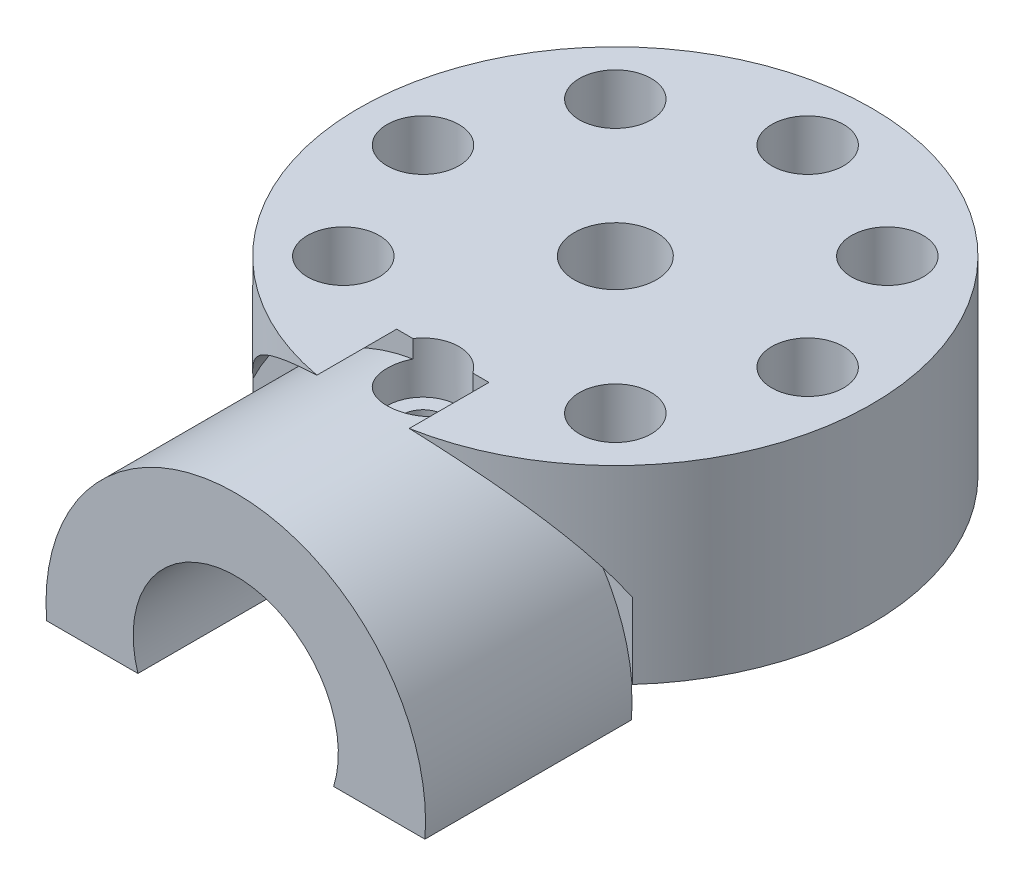
SolidWorks part; units mm, degrees
ref_plane "前视基准面" through (0, 0, 0) normal (0, 0, 1) x (1, 0, 0)
ref_plane "上视基准面" through (0, 0, 0) normal (0, 1, 0) x (1, 0, 0)
ref_plane "右视基准面" through (0, 0, 0) normal (1, 0, 0) x (0, 0, -1)
other "Configuration Table"
sketch "草图1" plane through (0, 0, 0) normal (0, 1, 0) x (1, 0, 0)
  line L0 (-25, 0) -> (25, 0) construction
  line L1 (0, 25) -> (0, -25) construction
  arc A2 (0, 25) -> (-25, 0) centre (0, 0) ccw
  arc A3 (-25, 0) -> (0, -25) centre (0, 0) ccw
  arc A4 (0, -25) -> (25, 0) centre (0, 0) ccw
  arc A5 (25, 0) -> (0, 25) centre (0, 0) ccw
  dimension "D1" = 25
  dimension "D2" = 90
extrude "凸台-拉伸2" add sketch "草图1" along normal blind 18.5
sketch "草图4" plane through (0, 0, 0) normal (0, 0, 1) x (1, 0, 0)
  line L0 (0, 0) -> (0, -1.5) construction
  line L1 (-25, 0) -> (25, 0) construction
  line L2 (-18.4391, 0) -> (18.4391, 0)
  arc A0 (-18.4391, 0) -> (18.4391, 0) centre (0, -1.5) cw
  dimension "D2" = 18.5
  dimension "D1" = 1.5
extrude "凸台-拉伸3" add sketch "草图4" along normal blind 37 contours A0 L2
sketch "草图7" plane through (0, 0, 0) normal (0, -1, 0) x (1, 0, 0)
  line L0 (-1000, 0) -> (49000, 0) construction
  line L1 (0, -1000) -> (0, 49000) construction
  line L2 (-707.1068, -707.1068) -> (34648.2323, 34648.2323) construction
  circle A0 centre (0, 0) radius 4
  circle A1 centre (0, 0) radius 18.75 construction
  circle A3 centre (18.75, 0) radius 2
  circle A4 centre (13.2583, 13.2583) radius 2
  circle A5 centre (0, 18.75) radius 2
  circle A6 centre (-18.75, 0) radius 2
  circle A7 centre (-13.2583, 13.2583) radius 2
  circle A8 centre (13.2583, -13.2583) radius 2
  circle A9 centre (0, -18.75) radius 2
  circle A10 centre (-13.2583, -13.2583) radius 2
  dimension "D1" = 37.5
  dimension "D2" = 8
  dimension "D4" = 4
  dimension "D5" = 4
  dimension "D3" = 45
extrude "切除-拉伸1" cut sketch "草图7" against normal through all
sketch "草图8" plane through (0, 0, 37) normal (0, 0, 1) x (1, 0, 0)
  line L0 (-18.4391, 0) -> (18.4391, 0)
  line L3 (18.4391, -3) -> (-18.4391, -3)
  line L4 (0, 0) -> (0, -3) construction
  arc A0 (18.4391, -3) -> (18.4391, 0) centre (0, -1.5) ccw
  arc A1 (-18.4391, 0) -> (-18.4391, -3) centre (0, -1.5) ccw
  dimension "D2" = 18.5
  dimension "D1" = 3
extrude "凸台-拉伸5" add sketch "草图8" against normal up to vertex
sketch "草图9" plane through (0, -3, 0) normal (0, -1, 0) x (1, 0, 0)
  circle A0 centre (0, 0) radius 25
extrude "切除-拉伸2" cut sketch "草图9" against normal up to surface (3 mm away) up to face at (0, 0, -4)
sketch "草图10" plane through (0, 0, 16.8152) normal (0, 0, 1) x (1, 0, 0)
  line L0 (0, 0) -> (0, -1.5) construction
  circle A2 centre (0, -1.5) radius 20.5
  circle A3 centre (0, -1.5) radius 18.5
  dimension "D2" = 37
  dimension "D3" = 41
  dimension "D1" = 1.5
extrude "切除-拉伸3" cut sketch "草图10" along normal up to surface (20.1848 mm away) up to face at (0, 7, 37)
sketch "草图11" plane through (0, 18.5, 0) normal (0, 1, 0) x (1, 0, 0)
  circle A0 centre (0, 18.75) radius 3.5
  circle A1 centre (13.2583, 13.2583) radius 3.5
  circle A2 centre (18.75, 0) radius 3.5
  circle A3 centre (13.2583, -13.2583) radius 3.5
  circle A4 centre (0, -18.75) radius 3.5
  circle A5 centre (-13.2583, -13.2583) radius 3.5
  circle A6 centre (-18.75, 0) radius 3.5
  circle A7 centre (-13.2583, 13.2583) radius 3.5
  dimension "D1" = 7
  dimension "D2" = 7
  dimension "D3" = 7
  dimension "D4" = 7
  dimension "D5" = 7
  dimension "D6" = 7
  dimension "D7" = 7
  dimension "D8" = 7
extrude "切除-拉伸4" cut sketch "草图11" against normal blind 5
sketch "草图12" plane through (0, 0, 0) normal (0, -1, 0) x (1, 0, 0)
  line L6 (0, 22) -> (-2.8146, 20.375)
  line L7 (-2.8146, 20.375) -> (-2.8146, 17.125)
  line L8 (-2.8146, 17.125) -> (0, 15.5)
  line L9 (0, 15.5) -> (2.8146, 17.125)
  line L10 (2.8146, 17.125) -> (2.8146, 20.375)
  line L11 (2.8146, 20.375) -> (0, 22)
  line L12 (0, -1000) -> (0, 49000) construction
  line L13 (-1000, 0) -> (49000, 0) construction
  line L14 (-707.1068, -707.1068) -> (34648.2323, 34648.2323) construction
  line L15 (707.1068, -707.1068) -> (-34648.2323, 34648.2323) construction
  line L16 (-382.6834, -923.8795) -> (18751.4882, 45270.0971) construction
  line L17 (12.4171, 16.3975) -> (15.5563, 15.5563)
  line L18 (10.119, 14.0994) -> (12.4171, 16.3975)
  line L19 (10.9602, 10.9602) -> (10.119, 14.0994)
  line L20 (14.0994, 10.119) -> (10.9602, 10.9602)
  line L21 (16.3975, 12.4171) -> (14.0994, 10.119)
  line L22 (15.5563, 15.5563) -> (16.3975, 12.4171)
  line L23 (-15.5563, 15.5563) -> (-16.3975, 12.4171)
  line L24 (-16.3975, 12.4171) -> (-14.0994, 10.119)
  line L25 (-14.0994, 10.119) -> (-10.9602, 10.9602)
  line L26 (-10.9602, 10.9602) -> (-10.119, 14.0994)
  line L27 (-10.119, 14.0994) -> (-12.4171, 16.3975)
  line L28 (-12.4171, 16.3975) -> (-15.5563, 15.5563)
  line L29 (16.3975, -12.4171) -> (15.5563, -15.5563)
  line L30 (14.0994, -10.119) -> (16.3975, -12.4171)
  line L31 (10.9602, -10.9602) -> (14.0994, -10.119)
  line L32 (10.119, -14.0994) -> (10.9602, -10.9602)
  line L33 (12.4171, -16.3975) -> (10.119, -14.0994)
  line L34 (15.5563, -15.5563) -> (12.4171, -16.3975)
  line L35 (20.375, 2.8146) -> (22, 0)
  line L36 (17.125, 2.8146) -> (20.375, 2.8146)
  line L37 (15.5, 0) -> (17.125, 2.8146)
  line L38 (17.125, -2.8146) -> (15.5, 0)
  line L39 (20.375, -2.8146) -> (17.125, -2.8146)
  line L40 (22, 0) -> (20.375, -2.8146)
  line L41 (-17.125, 2.8146) -> (-15.5, 0)
  line L42 (-15.5, 0) -> (-17.125, -2.8146)
  line L43 (0, -22) -> (2.8146, -20.375)
  line L44 (2.8146, -20.375) -> (2.8146, -17.125)
  line L45 (2.8146, -17.125) -> (0, -15.5)
  line L46 (0, -15.5) -> (-2.8146, -17.125)
  line L47 (-2.8146, -17.125) -> (-2.8146, -20.375)
  line L48 (-2.8146, -20.375) -> (0, -22)
  line L49 (-15.5563, -15.5563) -> (-12.4171, -16.3975)
  line L50 (-12.4171, -16.3975) -> (-10.119, -14.0994)
  line L51 (-10.119, -14.0994) -> (-10.9602, -10.9602)
  line L52 (-10.9602, -10.9602) -> (-14.0994, -10.119)
  line L53 (-14.0994, -10.119) -> (-16.3975, -12.4171)
  line L54 (-16.3975, -12.4171) -> (-15.5563, -15.5563)
  line L55 (-20.375, -2.8146) -> (-22, 0)
  line L56 (-17.125, -2.8146) -> (-20.375, -2.8146)
  line L57 (-20.375, 2.8146) -> (-17.125, 2.8146)
  line L58 (-22, 0) -> (-20.375, 2.8146)
  circle A0 centre (0, 18.75) radius 3.25 construction
  dimension "D1" = 6.5
  dimension "D2" = 120
  dimension "D3" = 45
  dimension "D4" = 45
  dimension "D5" = 22.5
extrude "切除-拉伸5" cut sketch "草图12" against normal blind 3
ref_plane "基准面1" through (0, 0, 10) normal (0, 0, 1) x (1, 0, 0)
sketch "草图13" plane through (0, 0, 10) normal (0, 0, 1) x (1, 0, 0)
  circle A0 centre (0, 0) radius 10
  dimension "D1" = 20
extrude "切除-拉伸7" cut sketch "草图13" along normal through all
